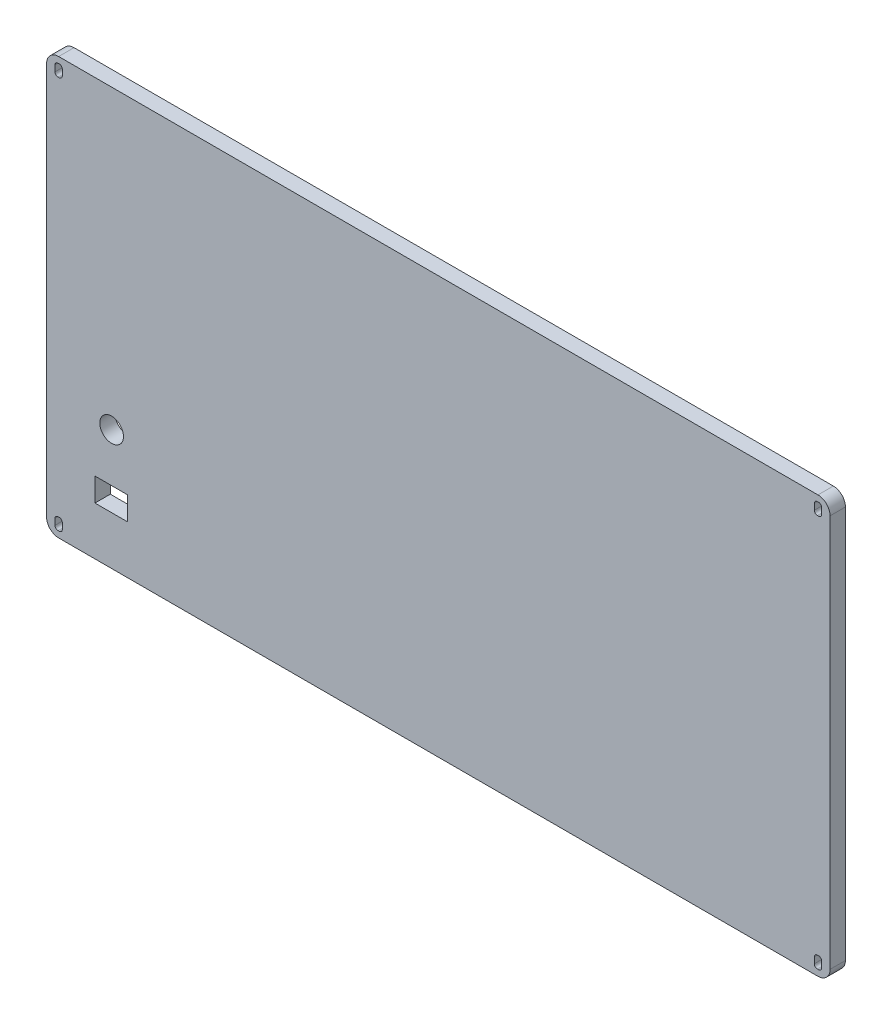
SolidWorks part; units mm, degrees
ref_plane "Front Plane" through (0, 0, 0) normal (0, 0, 1) x (1, 0, 0)
ref_plane "Top Plane" through (0, 0, 0) normal (0, 1, 0) x (1, 0, 0)
ref_plane "Right Plane" through (0, 0, 0) normal (1, 0, 0) x (0, 0, -1)
sketch "Sketch1" plane through (0, 0, 0) normal (0, 0, 1) x (1, 0, 0)
  line L0 (339.8604, -207.3242) -> (338.8604, -207.3242)
  line L1 (-298.3396, 132.3538) -> (349.3604, 132.3538)
  line L2 (-298.3396, 132.3538) -> (-298.3396, -212.3242)
  line L3 (-298.3396, -212.3242) -> (349.3604, -212.3242)
  line L4 (349.3604, 132.3538) -> (349.3604, -212.3242)
  line L5 (342.3604, -204.8242) -> (342.3604, -199.8242)
  line L6 (339.8604, -197.3242) -> (338.8604, -197.3242)
  line L7 (336.3604, -204.8242) -> (336.3604, -199.8242)
  line L8 (339.3604, -197.3242) -> (339.3604, -207.3242) construction
  line L9 (336.3604, -202.3242) -> (342.3604, -202.3242) construction
  line L10 (-287.8396, -207.3242) -> (-288.8396, -207.3242)
  line L11 (-291.3396, -204.8242) -> (-291.3396, -199.8242)
  line L12 (-287.8396, -197.3242) -> (-288.8396, -197.3242)
  line L13 (-285.3396, -204.8242) -> (-285.3396, -199.8242)
  line L14 (-287.8396, 117.3558) -> (-288.8396, 117.3558)
  line L15 (-291.3396, 119.8558) -> (-291.3396, 124.8558)
  line L16 (-287.8396, 127.3558) -> (-288.8396, 127.3558)
  line L17 (-285.3396, 119.8558) -> (-285.3396, 124.8558)
  line L18 (339.8604, 117.3558) -> (338.8604, 117.3558)
  line L19 (336.3604, 119.8558) -> (336.3604, 124.8558)
  line L20 (339.8604, 127.3558) -> (338.8604, 127.3558)
  line L21 (342.3604, 119.8558) -> (342.3604, 124.8558)
  line L23 (-258.3396, -152.9694) -> (-231.2378, -152.9694)
  line L24 (-258.3396, -152.9694) -> (-258.3396, -172.3242)
  line L25 (-258.3396, -172.3242) -> (-231.2378, -172.3242)
  line L26 (-231.2378, -152.9694) -> (-231.2378, -172.3242)
  arc A0 (339.8604, -207.3242) -> (342.3604, -204.8242) centre (339.8604, -204.8242) ccw
  arc A1 (342.3604, -199.8242) -> (339.8604, -197.3242) centre (339.8604, -199.8242) ccw
  arc A2 (338.8604, -207.3242) -> (336.3604, -204.8242) centre (338.8604, -204.8242) cw
  arc A3 (338.8604, -197.3242) -> (336.3604, -199.8242) centre (338.8604, -199.8242) ccw
  arc A4 (-288.8396, -207.3242) -> (-291.3396, -204.8242) centre (-288.8396, -204.8242) cw
  arc A5 (-288.8396, -197.3242) -> (-291.3396, -199.8242) centre (-288.8396, -199.8242) ccw
  arc A6 (-285.3396, -199.8242) -> (-287.8396, -197.3242) centre (-287.8396, -199.8242) ccw
  arc A7 (-287.8396, -207.3242) -> (-285.3396, -204.8242) centre (-287.8396, -204.8242) ccw
  arc A8 (-288.8396, 117.3558) -> (-291.3396, 119.8558) centre (-288.8396, 119.8558) cw
  arc A9 (-288.8396, 127.3558) -> (-291.3396, 124.8558) centre (-288.8396, 124.8558) ccw
  arc A10 (-285.3396, 124.8558) -> (-287.8396, 127.3558) centre (-287.8396, 124.8558) ccw
  arc A11 (-287.8396, 117.3558) -> (-285.3396, 119.8558) centre (-287.8396, 119.8558) ccw
  arc A12 (338.8604, 117.3558) -> (336.3604, 119.8558) centre (338.8604, 119.8558) cw
  arc A13 (338.8604, 127.3558) -> (336.3604, 124.8558) centre (338.8604, 124.8558) ccw
  arc A14 (342.3604, 124.8558) -> (339.8604, 127.3558) centre (339.8604, 124.8558) ccw
  arc A15 (339.8604, 117.3558) -> (342.3604, 119.8558) centre (339.8604, 119.8558) ccw
  circle A16 centre (-244.56, -112.9694) radius 9.779
  dimension "D6" = 2.5
  dimension "D17" = 40
  dimension "0.77" = 19.558
  dimension "D18" = 53.7797
  dimension "D1" = 647.7
  dimension "D2" = 132.3538
  dimension "12in" = 344.678
  dimension "D3" = 298.3396
  dimension "D4" = 6
  dimension "D5" = 10
  dimension "D7" = 10
  dimension "D8" = 10
  dimension "D11" = 7
  dimension "D12" = 4.998
  dimension "D13" = 7
  dimension "D14" = 27.1018
  dimension "D15" = 40
  dimension "0" = 19.3548
  dimension "D16" = 40
  dimension "D9" = 2
  dimension "D10" = 2
extrude "Boss-Extrude1" add sketch "Sketch1" along normal blind 12.7
fillet "Fillet1" radius 10 3 edges at (349.3604, -212.3242, 6.35) (349.3604, 132.3538, 6.35) (-298.3396, 132.3538, 6.35)
fillet "Fillet2" radius 10 1 edges at (-298.3396, -212.3242, 6.35)
